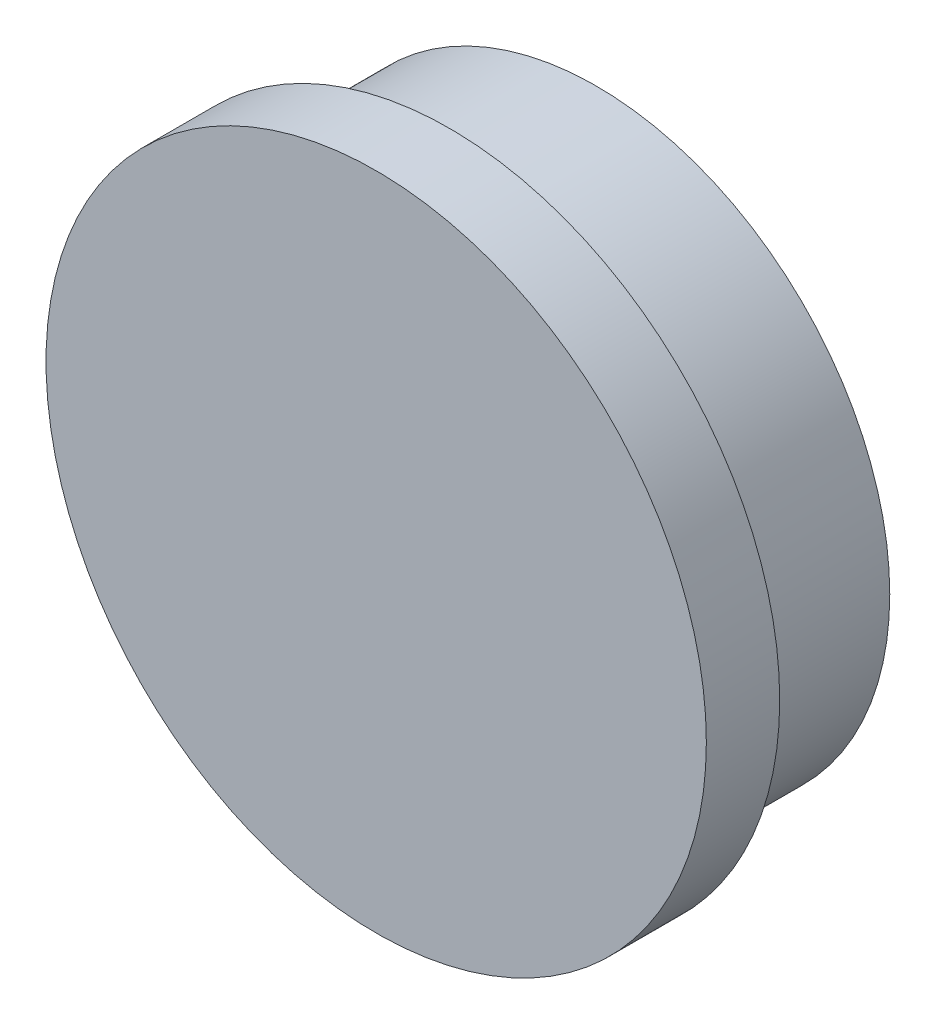
SolidWorks part; units mm, degrees
ref_plane "Front Plane" through (0, 0, 0) normal (0, 0, 1) x (1, 0, 0)
ref_plane "Top Plane" through (0, 0, 0) normal (0, 1, 0) x (1, 0, 0)
ref_plane "Right Plane" through (0, 0, 0) normal (1, 0, 0) x (0, 0, -1)
sketch "Sketch1" plane through (0, 0, 0) normal (0, 0, 1) x (1, 0, 0)
  circle A0 centre (0, 0) radius 11.25
  dimension "D1" = 22.5
extrude "Boss-Extrude1" add sketch "Sketch1" along normal blind 2.5
sketch "Sketch2" plane through (0, 0, 2.5) normal (0, 0, 1) x (1, 0, 0)
  circle A0 centre (0, 0) radius 10
  dimension "D1" = 20
extrude "Boss-Extrude2" add sketch "Sketch2" against normal blind 7.5
